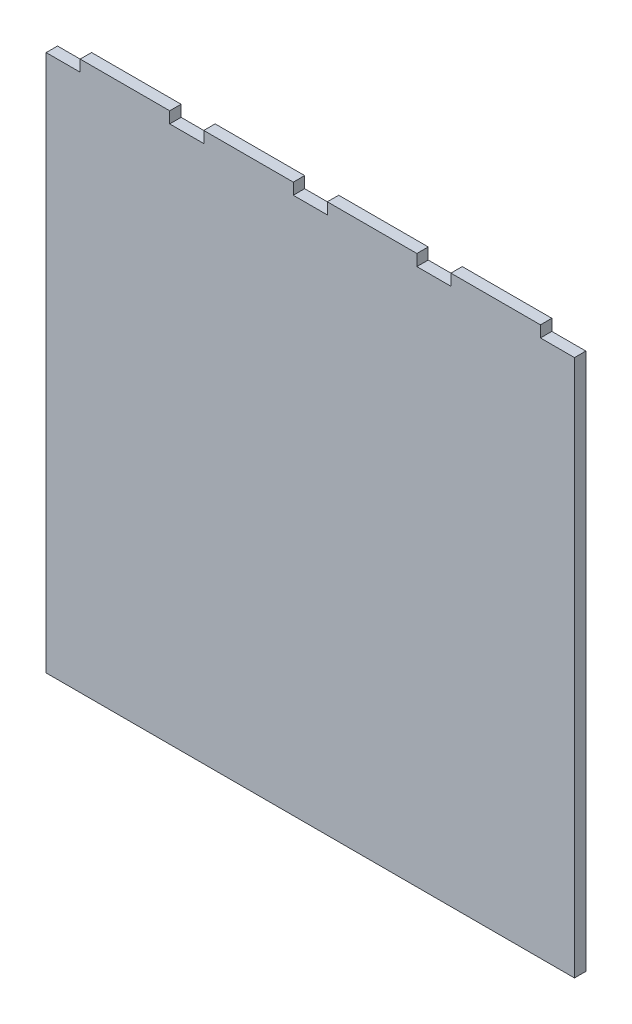
SolidWorks part; units mm, degrees
material "Beech"
ref_plane "Front Plane" through (0, 0, 0) normal (0, 0, 1) x (1, 0, 0)
ref_plane "Top Plane" through (0, 0, 0) normal (0, 1, 0) x (1, 0, 0)
ref_plane "Right Plane" through (0, 0, 0) normal (1, 0, 0) x (0, 0, -1)
sketch "Sketch2" plane through (0, 0, 0) normal (0, 0, 1) x (1, 0, 0)
  line L1 (0, 0) -> (19, 0)
  line L2 (0, 0) -> (0, -300)
  line L3 (0, -300) -> (295, -300)
  line L4 (295, 0) -> (295, -300)
  line L6 (19, 0) -> (19, 6.35)
  line L7 (19, 6.35) -> (69, 6.35)
  line L8 (69, 0) -> (69, 6.35)
  line L9 (88, 0) -> (88, 6.35)
  line L10 (88, 6.35) -> (138, 6.35)
  line L11 (138, 0) -> (138, 6.35)
  line L13 (157, 0) -> (157, 6.35)
  line L14 (157, 6.35) -> (207, 6.35)
  line L15 (207, 0) -> (207, 6.35)
  line L17 (226, 0) -> (226, 6.35)
  line L18 (226, 6.35) -> (276, 6.35)
  line L19 (276, 0) -> (276, 6.35)
  line L20 (69, 0) -> (88, 0)
  line L21 (138, 0) -> (157, 0)
  line L22 (207, 0) -> (226, 0)
  line L23 (276, 0) -> (295, 0)
  dimension "D1" = 295
  dimension "D2" = 300
  dimension "D3" = 6.35
  dimension "D4" = 50
  dimension "D5" = 19
  dimension "D7" = 19
  dimension "D6" = 4
extrude "Boss-Extrude1" add sketch "Sketch2" along normal blind 6.35
